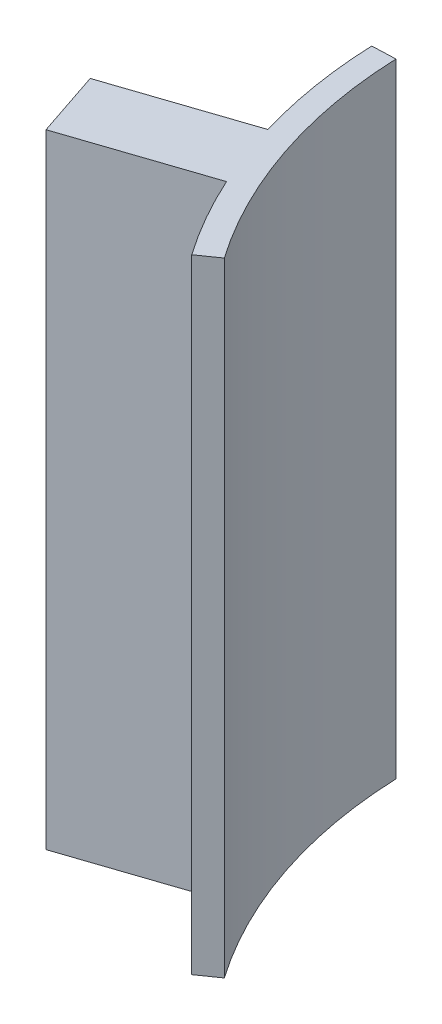
SolidWorks part; units mm, degrees
ref_plane "Front Plane" through (0, 0, 0) normal (0, 0, 1) x (1, 0, 0)
ref_plane "Top Plane" through (0, 0, 0) normal (0, 1, 0) x (1, 0, 0)
ref_plane "Right Plane" through (0, 0, 0) normal (1, 0, 0) x (0, 0, -1)
sketch "Sketch1" plane through (0, 0, 0) normal (0, 1, 0) x (1, 0, 0)
  line L0 (-61.9558, -2.3401) -> (-64.9537, -2.4533) construction
  line L1 (-61.9558, -2.3401) -> (-64.9537, -2.4533)
  line L2 (-53.3079, -37.1923) -> (-50.8475, -35.4757)
  line L4 (-76.5488, -32.6493) -> (-79.4094, -24.116)
  line L5 (-79.4094, -24.116) -> (-62.3429, -18.3947)
  line L6 (-76.5488, -32.6493) -> (-59.2024, -26.8342)
  arc A0 (-61.9558, -2.3401) -> (-50.8475, -35.4757) centre (0, 0) ccw
  arc A1 (-64.9537, -2.4533) -> (-62.3429, -18.3947) centre (0, 0) ccw
  arc A2 (-62.3429, -18.3947) -> (-64.9537, -2.4533) centre (0, 0) cw
  arc A3 (-62.3429, -18.3947) -> (-64.9537, -2.4533) centre (0, 0) cw
  arc A4 (-59.2024, -26.8342) -> (-53.3079, -37.1923) centre (0, 0) ccw
  arc A5 (-53.3079, -37.1923) -> (-59.2024, -26.8342) centre (0, 0) cw
  arc A6 (-53.3079, -37.1923) -> (-59.2024, -26.8342) centre (0, 0) cw
  point P13 (-77.9791, -28.3826)
  dimension "D1" = 4.5
extrude "Boss-Extrude1" add sketch "Sketch1" along normal blind 80 contours L6 A4 L2 A0 L1 A1 L5 L4
sketch "Sketch3" plane through (2.1058, 0, 6.2814) normal (0.3179, 0, 0.9481) x (0.9481, 0, -0.3179)
  line L1 (-82.9566, 80) -> (-75.4566, 80) construction
  line L2 (-82.9566, 80) -> (-82.9566, 55) construction
  line L3 (-82.9566, 55) -> (-75.4566, 55) construction
  line L4 (-75.4566, 80) -> (-75.4566, 55) construction
  line L5 (-82.9566, 0) -> (-145.9366, 0) construction
  line L6 (-82.9566, 0) -> (-82.9566, 25) construction
  line L7 (-82.9566, 25) -> (-145.9366, 25) construction
  line L8 (-145.9366, 0) -> (-145.9366, 25) construction
  line L9 (-82.9566, 0) -> (-75.4566, 0) construction
  line L10 (-82.9566, 0) -> (-82.9566, 25) construction
  line L11 (-82.9566, 25) -> (-75.4566, 25) construction
  line L12 (-75.4566, 0) -> (-75.4566, 25) construction
  dimension "D1" = 7.5
  dimension "D2" = 25
  dimension "D3" = 25
